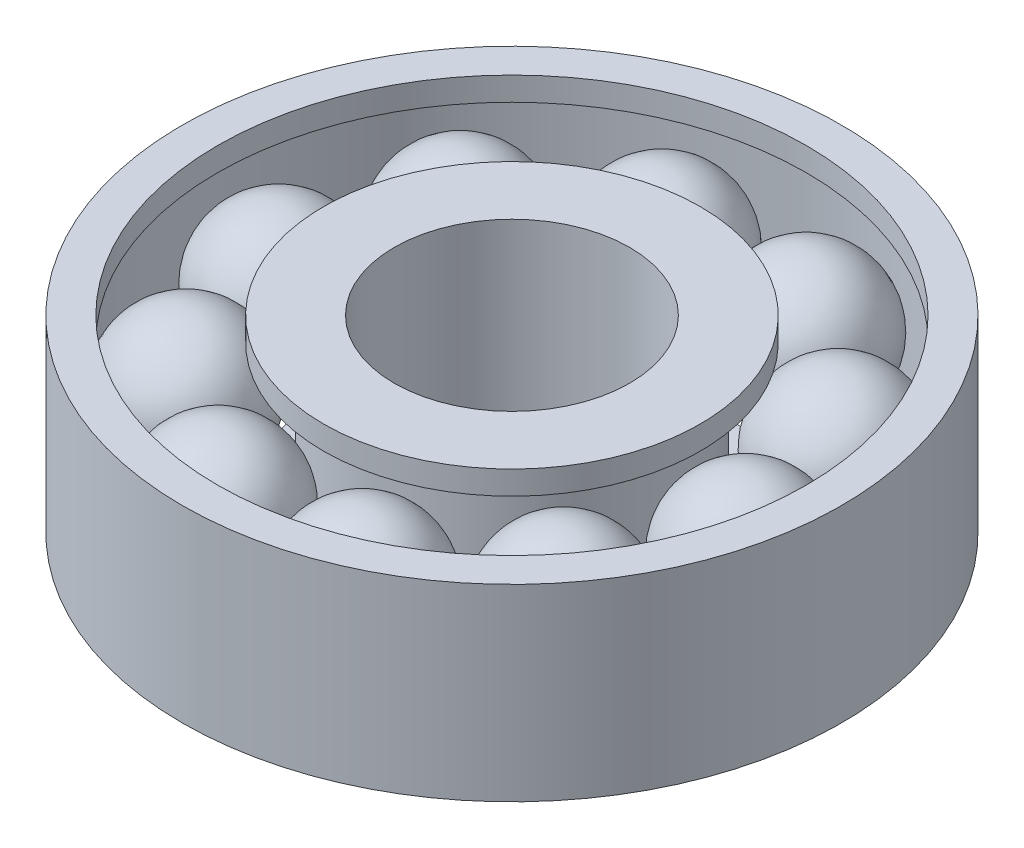
SolidWorks part; units mm, degrees
ref_plane "Front Plane" through (0, 0, 0) normal (0, 0, 1) x (1, 0, 0)
ref_plane "Top Plane" through (0, 0, 0) normal (0, 1, 0) x (1, 0, 0)
ref_plane "Right Plane" through (0, 0, 0) normal (1, 0, 0) x (0, 0, -1)
other "Graphic1"
other "Graphic (Closed) -1"
sketch "Sketch2" plane through (0, 0, 0) normal (0, 1, 0) x (1, 0, 0)
  circle A0 centre (0, 0) radius 12.5
  circle A1 centre (0, 0) radius 14
  dimension "D1" = 25
  dimension "D2" = 28
extrude "Boss-Extrude1" add sketch "Sketch2" along normal blind 8 from offset 3
sketch "Sketch5" plane through (0, 0, 0) normal (0, 1, 0) x (1, 0, 0)
  circle A0 centre (0, 0) radius 5
  circle A1 centre (0, 0) radius 8
  dimension "D1" = 10
  dimension "D2" = 16
extrude "Boss-Extrude2" add sketch "Sketch5" along normal blind 8 from offset 3 separate body
sketch "Sketch3" plane through (0, 0, 0) normal (0, 0, 1) x (1, 0, 0)
  line L0 (0, 11) -> (0, 3) construction
  line L1 (12.5, 11) -> (-12.5, 11) construction
  line L2 (-14, 3) -> (14, 3) construction
  line L4 (-13.25, 10) -> (-6.5, 10)
  line L5 (-13.25, 10) -> (-13.25, 4)
  line L6 (-13.25, 4) -> (-6.5, 4)
  line L8 (-6.5, 4) -> (-6.5, 10)
  line L11 (0, 9.5) -> (0, 4.5)
  line L12 (0, 9.5) -> (0, 4.5)
  point P6 (0, 7)
  dimension "D1" = 6
  dimension "D2" = 13.25
  dimension "D3" = 6.5
  dimension "D4" = 1
revolve "Cut-Revolve1" cut sketch "Sketch3" angle 360 about L0
sketch "Sketch6" plane through (0, 0, 0) normal (0, 0, 1) x (1, 0, 0)
  line L0 (7.2906, 10) -> (7.2906, 4) construction
  line L1 (-13.25, 10) -> (13.25, 10) construction
  line L2 (8, 4) -> (-8, 4) construction
  line L3 (9.9127, 7.2088) -> (13.2483, 7.2088) construction
  line L4 (9.5, 11) -> (10.3255, 11) construction
  line L5 (8, 11) -> (-8, 11) construction
  line L6 (12.5, 11) -> (-12.5, 11) construction
  line L7 (14, 11) -> (-14, 11) construction
  line L8 (9.9127, 11) -> (9.9127, 7.2088) construction
  line L9 (9.9127, 10.2088) -> (9.9127, 4.2088)
  arc A0 (9.9127, 4.2088) -> (9.9127, 10.2088) centre (9.9127, 7.2088) ccw
  arc A1 (7.2906, 8.6664) -> (7.2906, 5.7513) centre (9.9127, 7.2088) ccw
  point P17 (10.1795, 6.9309)
  point P22 (10.1462, 6.9976)
  point P23 (9.9461, 7.0199)
  point P24 (9.9127, 7.2088)
  dimension "D1" = 6
revolve "Revolve4" add sketch "Sketch6" angle 360 about L8
pattern_circular "CirPattern4" count 10 over 360 about axis through (0, 0, 0) along (0, 1, 0) of bodies 106
